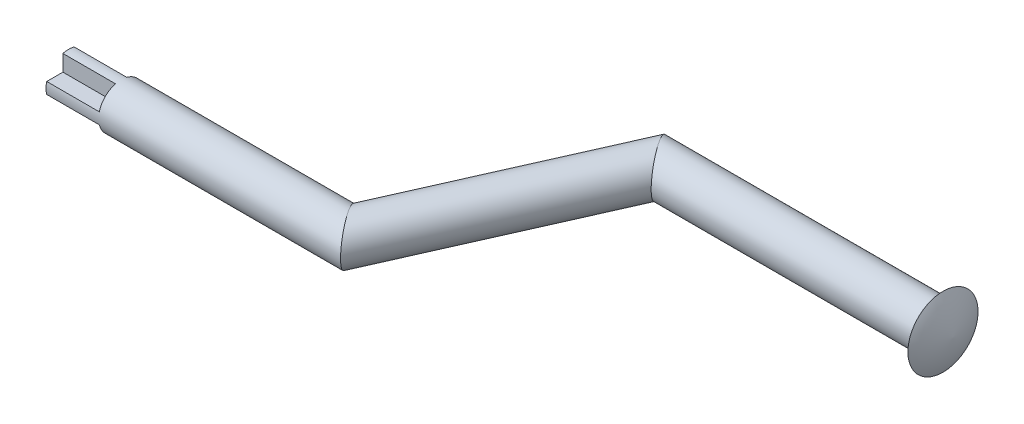
SolidWorks part; units mm, degrees
material "Stainless Steel (ferritic)"
ref_plane "Front Plane" through (0, 0, 0) normal (0, 0, 1) x (1, 0, 0)
ref_plane "Top Plane" through (0, 0, 0) normal (0, 1, 0) x (1, 0, 0)
ref_plane "Right Plane" through (0, 0, 0) normal (1, 0, 0) x (0, 0, -1)
sketch "Sketch1" plane through (0, 0, 0) normal (0, 1, 0) x (1, 0, 0)
  line L0 (0, 0) -> (-95.9849, 0)
  line L1 (-95.9849, 0) -> (-128.2526, -72.7462)
  line L2 (-128.2526, -72.7462) -> (-222.8823, -72.7462)
sketch "Sketch3" plane through (0, 0, 0) normal (1, 0, 0) x (0, 0, -1)
  circle A0 centre (0, 0) radius 7.62
  dimension "D1" = 15.24
sweep "Sweep1" add profiles "Sketch3" path "Sketch1"
sketch "Sketch4" plane through (-222.8823, 0, 0) normal (-1, 0, 0) x (0, 0, 1)
  line L0 (72.7462, 0) -> (80.3662, 0) construction
  line L1 (72.7462, 0) -> (72.7462, 7.62) construction
  line L2 (72.7462, 3.81) -> (76.5562, 3.81) construction
  line L3 (76.5562, 3.81) -> (76.5562, 0) construction
  line L4 (80.1242, 1.905) -> (74.6512, 1.905)
  line L5 (74.6512, 1.905) -> (74.6512, 7.378)
  circle A0 centre (72.7462, 0) radius 7.62 construction
  arc A3 (74.6512, 7.378) -> (80.1242, 1.905) centre (72.7462, 0) cw
  point P14 (74.6512, 3.81)
  point P15 (76.5562, 1.905)
sketch "Sketch5" plane through (-222.8823, 0, 0) normal (-1, 0, 0) x (0, 0, 1)
  line L0 (72.7462, 0) -> (72.7462, 7.62) construction
  line L1 (72.7462, 0) -> (72.7462, -7.62) construction
  line L2 (72.7462, 0) -> (65.1262, 0) construction
  line L3 (68.9362, 0) -> (68.9362, 3.81) construction
  line L4 (68.9362, 3.81) -> (72.7462, 3.81) construction
  line L5 (65.3681, 1.905) -> (70.8412, 1.905)
  line L6 (70.8412, 1.905) -> (70.8412, 7.378)
  circle A0 centre (72.7462, 0) radius 7.62 construction
  circle A1 centre (72.7462, 0) radius 7.62 construction
  arc A2 (65.3681, 1.905) -> (70.8412, 7.378) centre (72.7462, 0) cw
  circle A4 centre (72.7462, 0) radius 7.62 construction
  point P4 (68.9362, 1.905)
  point P5 (70.8412, 3.81)
sketch "Sketch6" plane through (0, 0, 0) normal (0, 1, 0) x (1, 0, 0)
  line L0 (0, 0) -> (15.434, 0) construction
  line L1 (0, 0) -> (0, 11.8605)
  line L2 (0, 0) -> (3.407, 0)
  arc A0 (0, 11.8605) -> (3.407, 0) centre (-27.0941, -2.342) cw
revolve "Revolve1" add sketch "Sketch6" angle 360 about L0
extrude "Cut-Extrude3" cut sketch "Sketch4" against normal blind 17.78
mirror "Mirror3" about plane through (0, 0, 0) normal (0, 1, 0) of "Cut-Extrude3"
extrude "Cut-Extrude4" cut sketch "Sketch5" against normal blind 17.78
mirror "Mirror4" about plane through (0, 0, 0) normal (0, 1, 0) of "Cut-Extrude4"
